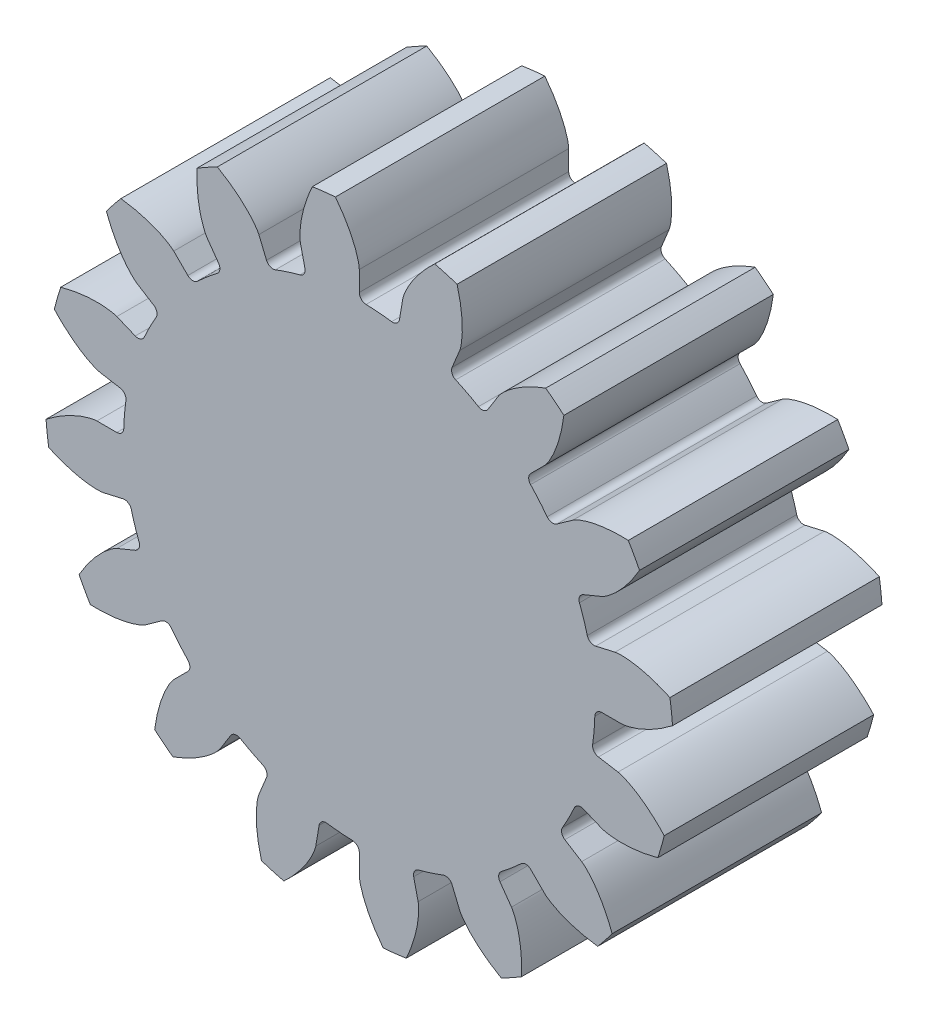
SolidWorks part; units mm, degrees
ref_plane "Front Plane" through (0, 0, 0) normal (0, 0, 1) x (1, 0, 0)
ref_plane "Top Plane" through (0, 0, 0) normal (0, 1, 0) x (1, 0, 0)
ref_plane "Right Plane" through (0, 0, 0) normal (1, 0, 0) x (0, 0, -1)
sketch "Sketch1" plane through (0, 0, 0) normal (0, 0, 1) x (1, 0, 0)
  circle A0 centre (0, 0) radius 4.5
  dimension "D1" = 9
extrude "Boss-Extrude1" add sketch "Sketch1" along normal blind 3
sketch "Sketch3" plane through (0, 0, 0) normal (0, 0, 1) x (1, 0, 0)
  line L0 (3.375, 0) -> (3.7588, 0)
  line L2 (3.3283, -0.5595) -> (3.7068, -0.6231)
  line L3 (0, 0) -> (-4.4844, 0.3743) construction
  circle A0 centre (0, 0) radius 4 construction
  circle A1 centre (0, 0) radius 3.7588 construction
  arc A2 (3.3283, -0.5595) -> (3.375, 0) centre (0, 0) ccw
  circle A3 centre (0, 0) radius 4.5 construction
  spline S0 degree 4 poles (3.7588, 0) (3.7624, 0.0001) (3.7692, 0.0005) (3.7803, 0.0014) (3.8021, 0.0042) (3.8267, 0.0084) (3.8544, 0.0143) (3.884, 0.0218) (3.9091, 0.0289) (3.9342, 0.0366) (3.959, 0.0448) (3.9889, 0.0554) (4.0246, 0.0691) (4.066, 0.0865) (4.1126, 0.1078) (4.1597, 0.1312) (4.2056, 0.1556) (4.2515, 0.1818) (4.2956, 0.2083) (4.3408, 0.2374) (4.3823, 0.2651) (4.4282, 0.2979) (4.465, 0.3248) (4.5129, 0.3622) (4.5409, 0.3848) (4.5735, 0.4119) (4.5878, 0.4243) (4.5966, 0.4319) knots 0 0 0 0 0 0.015084 0.028532 0.04661 0.092111 0.119476 0.146842 0.174209 0.201575 0.228941 0.256307 0.307035 0.361767 0.4165 0.471232 0.525964 0.580697 0.635429 0.690161 0.744894 0.799626 0.854358 0.909091 0.954545 1 1 1 1 1 construction
  spline S1 degree 4 poles (3.7588, 0) (3.7624, 0.0001) (3.7692, 0.0005) (3.7803, 0.0014) (3.8021, 0.0042) (3.8267, 0.0084) (3.8544, 0.0143) (3.884, 0.0218) (3.9091, 0.0289) (3.9342, 0.0366) (3.959, 0.0448) (3.9889, 0.0554) (4.0246, 0.0691) (4.066, 0.0865) (4.1126, 0.1078) (4.1597, 0.1312) (4.2056, 0.1556) (4.2515, 0.1818) (4.2956, 0.2083) (4.3408, 0.2374) (4.3823, 0.2651) (4.4282, 0.2979) (4.465, 0.3248) (4.5025, 0.3541) (4.5206, 0.3686) (4.5299, 0.376) knots 0 0 0 0 0 0.015084 0.028532 0.04661 0.092111 0.119476 0.146842 0.174209 0.201575 0.228941 0.256307 0.307035 0.361767 0.4165 0.471232 0.525964 0.580697 0.635429 0.690161 0.744894 0.799626 0.854358 0.909091 0.909091 0.909091 0.909091 0.909091
  spline S2 degree 4 poles (3.7068, -0.6231) (3.7103, -0.6237) (3.717, -0.6253) (3.7277, -0.6281) (3.7488, -0.6344) (3.7724, -0.6427) (3.7987, -0.6531) (3.8266, -0.6653) (3.8503, -0.6765) (3.8737, -0.6882) (3.8968, -0.7005) (3.9245, -0.7159) (3.9575, -0.7353) (3.9954, -0.7593) (4.0379, -0.7881) (4.0804, -0.8189) (4.1216, -0.8506) (4.1625, -0.8841) (4.2016, -0.9175) (4.2414, -0.9537) (4.2777, -0.9879) (4.3175, -1.0278) (4.3494, -1.0605) (4.3904, -1.1053) (4.4143, -1.1323) (4.4419, -1.1644) (4.454, -1.1789) (4.4614, -1.1879) knots 0 0 0 0 0 0.015084 0.028532 0.04661 0.092111 0.119476 0.146842 0.174209 0.201575 0.228941 0.256307 0.307035 0.361767 0.4165 0.471232 0.525964 0.580697 0.635429 0.690161 0.744894 0.799626 0.854358 0.909091 0.954545 1 1 1 1 1 construction
  spline S3 degree 4 poles (3.7068, -0.6231) (3.7103, -0.6237) (3.717, -0.6253) (3.7277, -0.6281) (3.7488, -0.6344) (3.7724, -0.6427) (3.7987, -0.6531) (3.8266, -0.6653) (3.8503, -0.6765) (3.8737, -0.6882) (3.8968, -0.7005) (3.9245, -0.7159) (3.9575, -0.7353) (3.9954, -0.7593) (4.0379, -0.7881) (4.0804, -0.8189) (4.1216, -0.8506) (4.1625, -0.8841) (4.2016, -0.9175) (4.2414, -0.9537) (4.2777, -0.9879) (4.3175, -1.0278) (4.3494, -1.0605) (4.3815, -1.0956) (4.397, -1.1129) (4.4049, -1.1218) knots 0 0 0 0 0 0.015084 0.028532 0.04661 0.092111 0.119476 0.146842 0.174209 0.201575 0.228941 0.256307 0.307035 0.361767 0.4165 0.471232 0.525964 0.580697 0.635429 0.690161 0.744894 0.799626 0.854358 0.909091 0.909091 0.909091 0.909091 0.909091
  point P5 (3.375, 0)
  point P11 (3.3283, -0.5595)
  dimension "D1" = 8
  dimension "D2" = 7.5175
  dimension "D3" = 6.75
  dimension "D4" = 4.771
  dimension "D5" = 4.771
extrude "Cut-Extrude1" cut sketch "Sketch3" against normal through all and the other way through all
fillet "Fillet1" radius 0.1 1 edges at (3.3283, -0.5595, 1.5)
fillet "Fillet2" radius 0.1 1 edges at (3.375, 0, 1.5)
pattern_circular "CirPattern14" count 16 over 360 about axis through (0, 0, 3) along (0, 0, -1) of "Cut-Extrude1", "Fillet1", "Fillet2"
equation "\"P\" = 2'Diametral Pitch"
equation "\"N\"= 16'Number of teeth"
equation "\"phi\"= 20deg'pressure angle"
equation "\"a\"= 1 / \"P\"'addendum"
equation "\"b\"= 1.25 / \"P\"'dedendum"
equation "\"c\"= \"b\" - \"a\"'clearance"
equation "\"dp\"= \"N\" / \"P\"'pitch circle diameter"
equation "\"db\"= \"dp\" * cos ( \"phi\" )'base circle diameter"
equation "\"D1@Sketch1\"= \"dp\" + 2 * \"a\"'Addendum circle diameter"
equation "\"D1@Sketch3\"= \"dp\"'pitch circle"
equation "\"D2@Sketch3\"= \"db\" 'base circle"
equation "\"D3@Sketch3\" = \"dp\" - 2 * \"b\"'dedendum circle"
equation "\"alpha\"= sqr ( \"dp\" ^ 2 - \"db\" ^ 2 ) / \"db\" * 180 / pi - \"phi\"'alpha (deg)"
equation "\"beta\"= ( 360 / ( 4 * \"N\" ) - \"alpha\" ) * 2"
equation "\"D4@Sketch3\"= 360 / ( 4 * \"N\" ) - \"alpha\""
equation "\"D5@Sketch3\"= 360 / ( 4 * \"N\" ) - \"alpha\""
